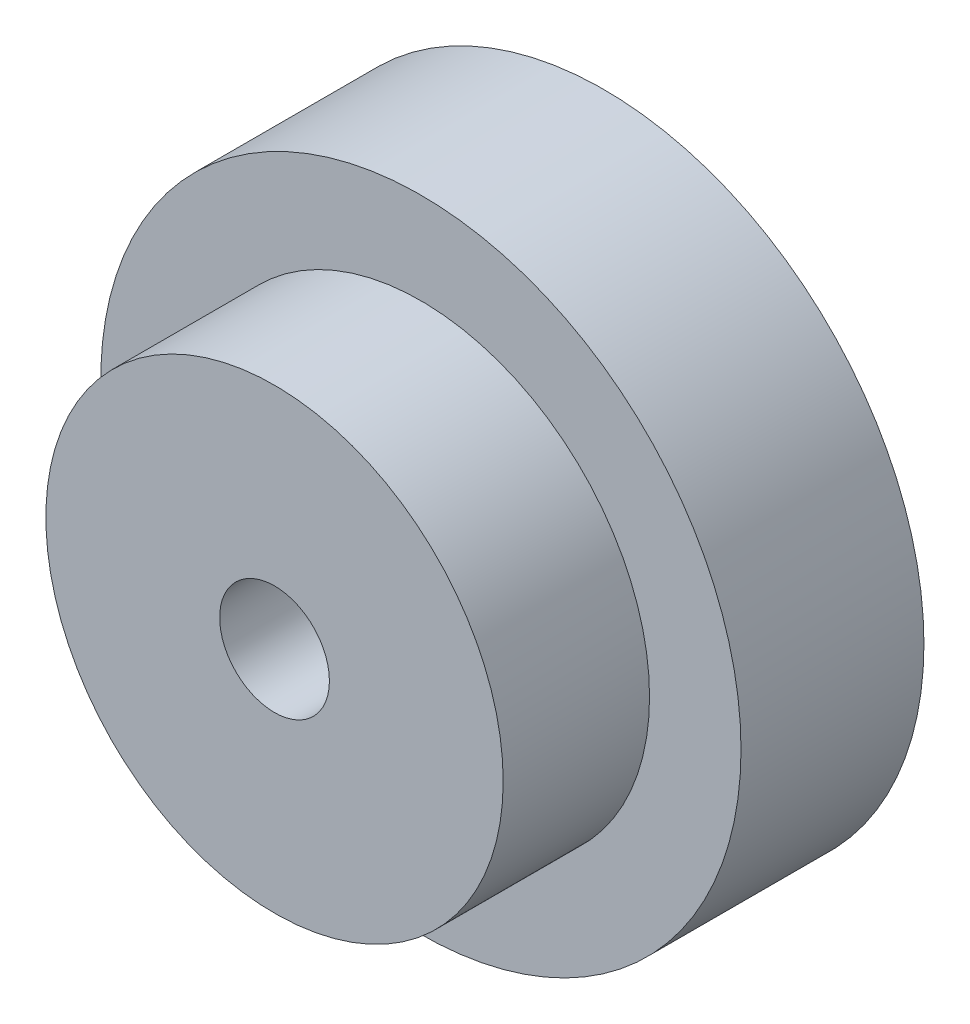
SolidWorks part; units mm, degrees
ref_plane "前视基准面" through (0, 0, 0) normal (0, 0, 1) x (1, 0, 0)
ref_plane "上视基准面" through (0, 0, 0) normal (0, 1, 0) x (1, 0, 0)
ref_plane "右视基准面" through (0, 0, 0) normal (1, 0, 0) x (0, 0, -1)
sketch "草图1" plane through (0, 0, 0) normal (0, 0, 1) x (1, 0, 0)
  circle A0 centre (0, 0) radius 17.5
  circle A1 centre (0, 0) radius 3
extrude "凸台-拉伸1" add sketch "草图1" along normal blind 10
sketch "草图2" plane through (0, 0, 10) normal (0, 0, 1) x (1, 0, 0)
  circle A0 centre (0, 0) radius 12.5
  circle A1 centre (0, 0) radius 3
  dimension "D1" = 25
extrude "凸台-拉伸2" add sketch "草图2" along normal blind 8
